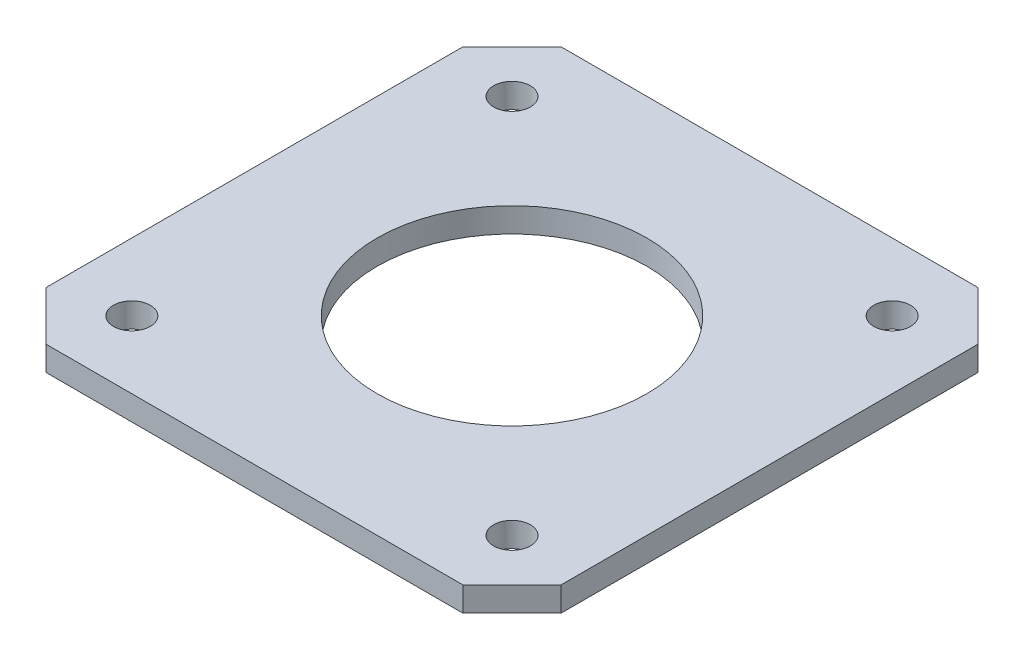
SolidWorks part; units mm, degrees
ref_plane "前视基准面" through (0, 0, 0) normal (0, 0, 1) x (1, 0, 0)
ref_plane "上视基准面" through (0, 0, 0) normal (0, 1, 0) x (1, 0, 0)
ref_plane "右视基准面" through (0, 0, 0) normal (1, 0, 0) x (0, 0, -1)
sketch "草图1" plane through (0, 9.9639, 0) normal (0, 1, 0) x (1, 0, 0)
  line L0 (39.0225, 61.1486) -> (35.0225, 57.1486) construction
  line L1 (35.0225, 57.1486) -> (35.0225, 23.1486) construction
  line L2 (35.0225, 23.1486) -> (39.0225, 19.1486) construction
  line L3 (39.0225, 19.1486) -> (73.0225, 19.1486) construction
  line L4 (73.0225, 19.1486) -> (77.0225, 23.1486) construction
  line L5 (77.0225, 23.1486) -> (77.0225, 57.1486) construction
  line L6 (77.0225, 57.1486) -> (73.0225, 61.1486) construction
  line L7 (73.0225, 61.1486) -> (39.0225, 61.1486) construction
  line L8 (39.0225, 61.1486) -> (35.0225, 57.1486)
  line L9 (35.0225, 57.1486) -> (35.0225, 23.1486)
  line L10 (35.0225, 23.1486) -> (39.0225, 19.1486)
  line L11 (39.0225, 19.1486) -> (73.0225, 19.1486)
  line L12 (73.0225, 19.1486) -> (77.0225, 23.1486)
  line L13 (77.0225, 23.1486) -> (77.0225, 57.1486)
  line L14 (77.0225, 57.1486) -> (73.0225, 61.1486)
  line L15 (73.0225, 61.1486) -> (39.0225, 61.1486)
  circle A0 centre (56.0225, 40.1486) radius 11 construction
  circle A3 centre (40.5225, 24.6486) radius 1.5 construction
  circle A4 centre (71.5225, 24.6486) radius 1.5 construction
  circle A5 centre (71.5225, 55.6486) radius 1.5 construction
  circle A6 centre (40.5225, 55.6486) radius 1.5 construction
  circle A7 centre (56.0225, 40.1486) radius 11
  circle A8 centre (40.5225, 24.6486) radius 1.5
  circle A9 centre (71.5225, 24.6486) radius 1.5
  circle A10 centre (71.5225, 55.6486) radius 1.5
  circle A11 centre (40.5225, 55.6486) radius 1.5
extrude "凸台-拉伸1" add sketch "草图1" along normal blind 2
